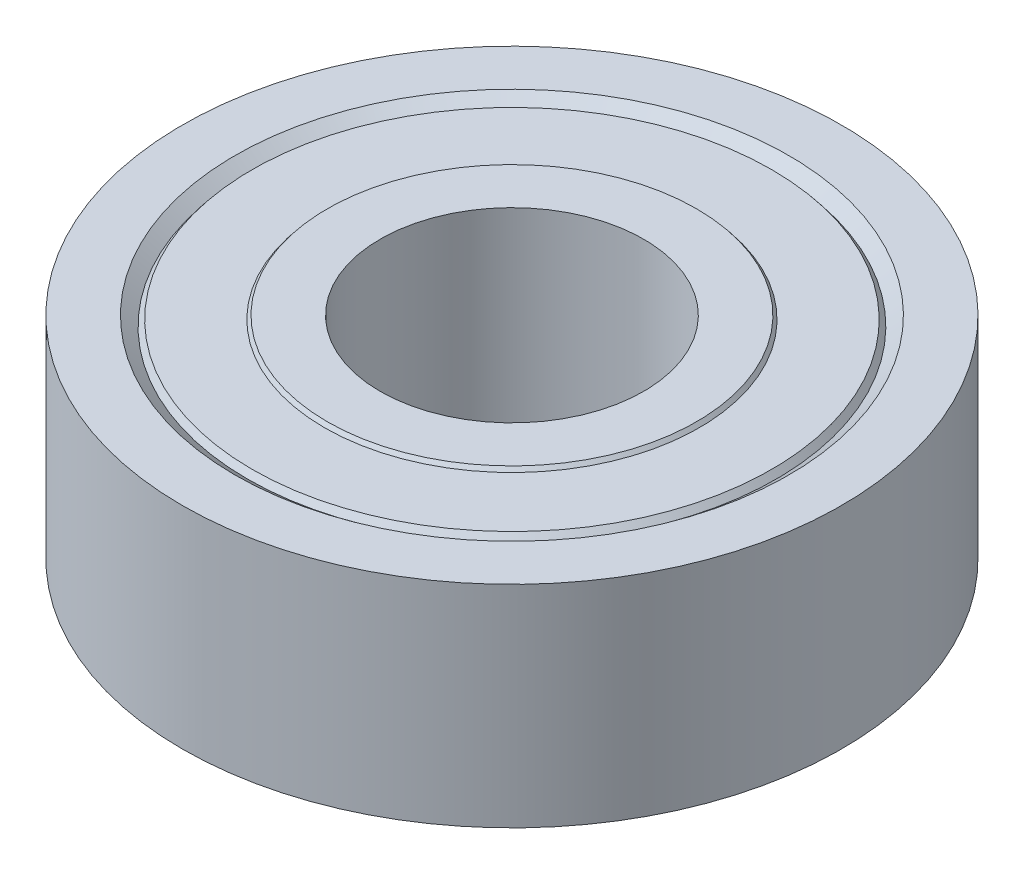
SolidWorks part; units mm, degrees
ref_plane "Front Plane" through (0, 0, 0) normal (0, 0, 1) x (1, 0, 0)
ref_plane "Top Plane" through (0, 0, 0) normal (0, 1, 0) x (1, 0, 0)
ref_plane "Right Plane" through (0, 0, 0) normal (1, 0, 0) x (0, 0, -1)
sketch "Sketch2" plane through (0, 0, 0) normal (0, 0, 1) x (1, 0, 0)
  line L0 (0, 0) -> (7.9375, 0)
  line L1 (7.9375, 0) -> (7.9375, 5.08)
  line L2 (7.9375, 5.08) -> (0, 5.08)
  line L3 (0, 5.08) -> (0, 0)
  line L4 (0, 0) -> (3.175, 0)
  line L5 (3.175, 0) -> (3.175, 5.08)
  line L6 (7.9375, 5.08) -> (6.6675, 5.08)
  line L7 (3.175, 5.08) -> (4.445, 5.08)
  line L8 (6.6675, 5.08) -> (6.368, 4.8468)
  line L9 (6.368, 4.8468) -> (6.255, 4.9919)
  line L10 (6.255, 4.9919) -> (4.5152, 4.9919)
  line L11 (4.5152, 4.9919) -> (4.445, 5.08)
  line L12 (3.175, 2.54) -> (4.6938, 2.54)
  line L13 (4.5152, 0.0881) -> (4.445, 0)
  line L14 (6.255, 0.0881) -> (4.5152, 0.0881)
  line L15 (6.368, 0.2332) -> (6.255, 0.0881)
  line L16 (6.6675, 0) -> (6.368, 0.2332)
  line L17 (3.175, 0) -> (4.445, 0)
  line L18 (7.9375, 0) -> (6.6675, 0)
  line L19 (7.9375, 0) -> (0, 0)
  dimension "D1" = 7.9375
revolve "Revolve1" add sketch "Sketch2" angle 360 about L3
